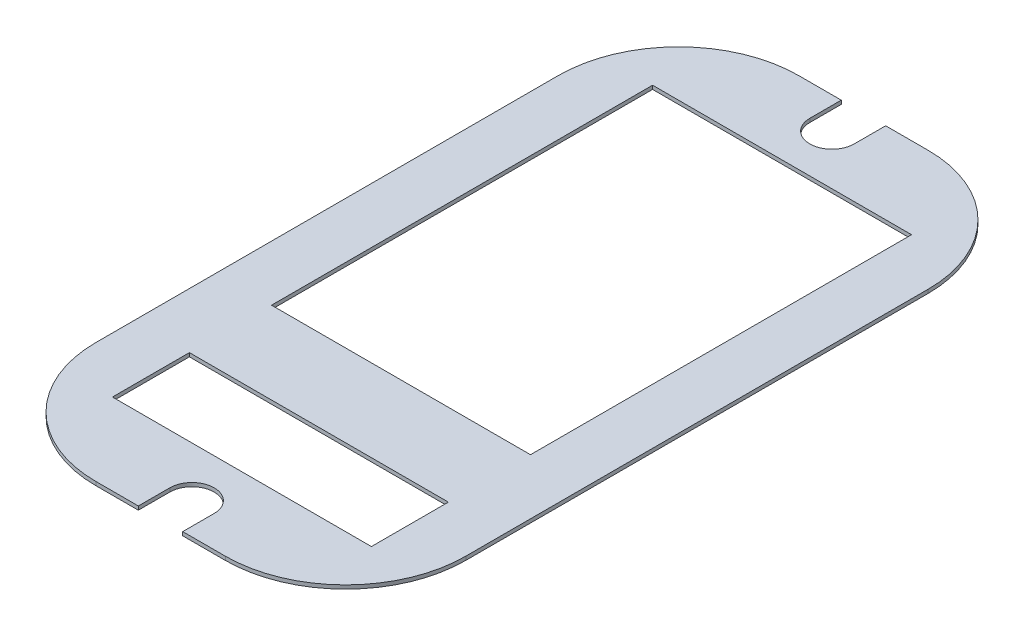
SolidWorks part; units mm, degrees
ref_plane "Front Plane" through (0, 0, 0) normal (0, 0, 1) x (1, 0, 0)
ref_plane "Top Plane" through (0, 0, 0) normal (0, 1, 0) x (1, 0, 0)
ref_plane "Right Plane" through (0, 0, 0) normal (1, 0, 0) x (0, 0, -1)
sketch "Sketch2" plane through (0, 0, 0) normal (0, 1, 0) x (1, 0, 0)
  line L0 (-0.6, 9.5) -> (-1.75, 9.5)
  line L1 (-5, 6.25) -> (-5, -6.25)
  line L2 (-1.75, -9.5) -> (-0.6, -9.5)
  line L3 (-3.5, -3) -> (3.5, -3)
  line L4 (3.5, -3) -> (3.5, 7.3)
  line L5 (3.5, 7.3) -> (-3.5, 7.3)
  line L6 (-3.5, 7.3) -> (-3.5, -3)
  line L7 (-3.5, -7.3) -> (3.5, -7.3)
  line L8 (3.5, -7.3) -> (3.5, -5.22)
  line L9 (3.5, -5.22) -> (-3.5, -5.22)
  line L10 (-3.5, -5.22) -> (-3.5, -7.3)
  line L11 (0, 8.65) -> (0, -8.65) construction
  line L12 (-0.6, -8.65) -> (-0.6, -9.5)
  line L13 (0.6, -8.65) -> (0.6, -9.5)
  line L14 (-0.6, 9.5) -> (-0.6, 8.65)
  line L15 (0.6, -9.5) -> (1.75, -9.5)
  line L16 (5, -6.25) -> (5, 6.25)
  line L17 (1.75, 9.5) -> (0.6, 9.5)
  line L18 (0, 0) -> (0, -3) construction
  line L19 (0, -3) -> (0, -5.22) construction
  line L20 (0.6, 9.5) -> (0.6, 8.65)
  arc A0 (-0.6, 8.65) -> (0.6, 8.65) centre (0, 8.65) ccw
  arc A1 (0.6, -8.65) -> (-0.6, -8.65) centre (0, -8.65) ccw
  arc A2 (-1.75, 9.5) -> (-5, 6.25) centre (-1.75, 6.25) ccw
  arc A3 (-5, -6.25) -> (-1.75, -9.5) centre (-1.75, -6.25) ccw
  arc A4 (1.75, -9.5) -> (5, -6.25) centre (1.75, -6.25) ccw
  arc A5 (5, 6.25) -> (1.75, 9.5) centre (1.75, 6.25) ccw
  point P30 (0, -5.22)
  point P31 (0, -3)
  point P38 (0, 0)
  dimension "D7" = 0.6
  dimension "D9" = 3.25
  dimension "D1" = 2.22
  dimension "D2" = 3
  dimension "D3" = 10.3
  dimension "D4" = 2.08
  dimension "D5" = 17.3
  dimension "D6" = 7
  dimension "D8" = 10
  dimension "D10" = 19
extrude "Boss-Extrude1" add sketch "Sketch2" along normal blind 0.1
